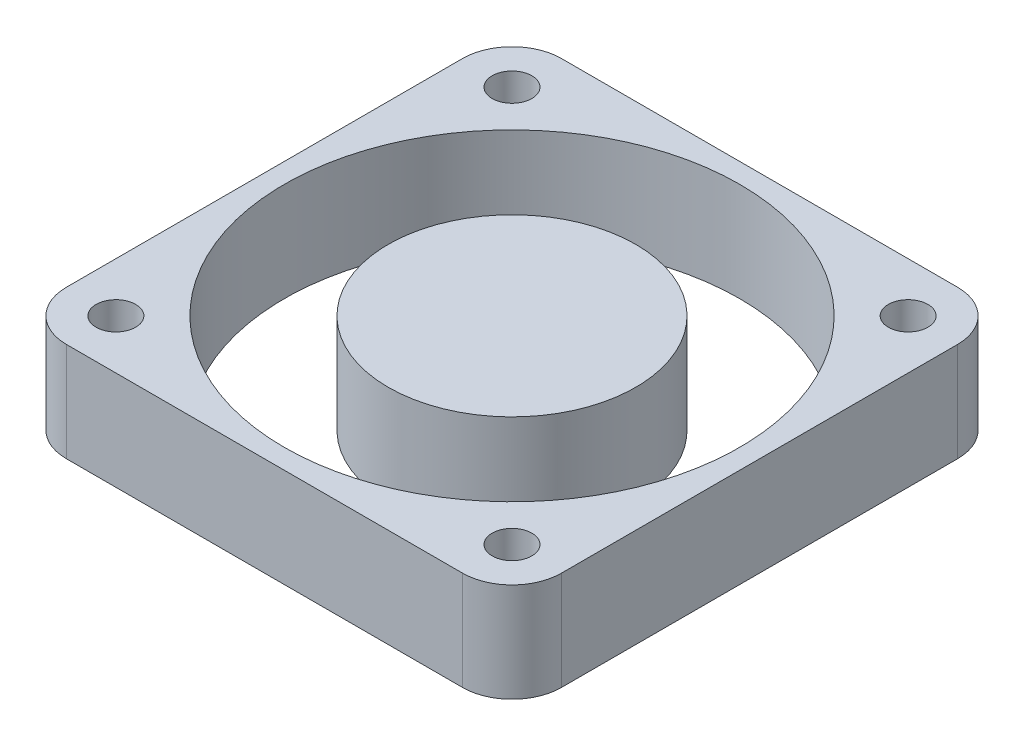
SolidWorks part; units mm, degrees
ref_plane "前视基准面" through (0, 0, 0) normal (0, 0, 1) x (1, 0, 0)
ref_plane "上视基准面" through (0, 0, 0) normal (0, 1, 0) x (1, 0, 0)
ref_plane "右视基准面" through (0, 0, 0) normal (1, 0, 0) x (0, 0, -1)
sketch "草图1" plane through (0, 0, 0) normal (0, 1, 0) x (1, 0, 0)
  line L0 (0, 74.7112) -> (0, -68.6123) construction
  line L1 (-20, 25) -> (20, 25)
  line L2 (-25, 20) -> (-25, -20)
  line L3 (-20, -25) -> (20, -25)
  line L4 (25, 20) -> (25, -20)
  line L5 (-53.6701, 0) -> (64.953, 0) construction
  arc A0 (25, 20) -> (20, 25) centre (20, 20) ccw
  arc A1 (-25, 20) -> (-20, 25) centre (-20, 20) cw
  arc A2 (-20, -25) -> (-25, -20) centre (-20, -20) cw
  arc A3 (25, -20) -> (20, -25) centre (20, -20) cw
  point P11 (25, 25)
  point P14 (-25, 25)
  point P17 (-25, -25)
  dimension "D3" = 5
  dimension "D4" = 5
  dimension "D1" = 50
  dimension "D2" = 50
extrude "拉伸1" add sketch "草图1" along normal blind 10
sketch "草图2" plane through (0, 10, 0) normal (0, 1, 0) x (-1, 0, 0)
  line L10 (-60.6024, 0) -> (52.7191, 0) construction
  line L11 (0, -57.861) -> (0, 57.0129) construction
  line L12 (-20, -23) -> (20, -23)
  line L13 (-23, 20) -> (-23, -20)
  line L14 (20, 23) -> (-20, 23)
  line L15 (23, -20) -> (23, 20)
  line L16 (-20, -23) -> (20, -23)
  line L17 (-23, 20) -> (-23, -20)
  line L18 (20, 23) -> (-20, 23)
  line L19 (23, -20) -> (23, 20)
  circle A8 centre (0, 0) radius 12.5
  arc A12 (-23, -20) -> (-20, -23) centre (-20, -20) ccw
  arc A13 (20, -23) -> (23, -20) centre (20, -20) ccw
  arc A14 (-20, 23) -> (-23, 20) centre (-20, 20) ccw
  arc A15 (23, 20) -> (20, 23) centre (20, 20) ccw
  arc A16 (-23, -20) -> (-20, -23) centre (-20, -20) ccw
  arc A17 (20, -23) -> (23, -20) centre (20, -20) ccw
  arc A18 (-20, 23) -> (-23, 20) centre (-20, 20) ccw
  arc A19 (23, 20) -> (20, 23) centre (20, 20) ccw
  dimension "D2" = 25
  dimension "D1" = 2
extrude "切除-拉伸1" cut sketch "草图2" against normal blind 17
sketch "草图3" plane through (0, 10, 0) normal (0, 1, 0) x (-1, 0, 0)
  line L0 (25, -20) -> (25, 20) construction
  line L1 (20, 25) -> (-20, 25) construction
  line L2 (-25, 20) -> (-25, -20) construction
  line L3 (-20, -25) -> (20, -25) construction
  line L4 (25, -20) -> (25, 20)
  line L5 (20, 25) -> (-20, 25)
  line L6 (-25, 20) -> (-25, -20)
  line L7 (-20, -25) -> (20, -25)
  circle A0 centre (0, 0) radius 23
  arc A1 (20, -25) -> (25, -20) centre (20, -20) ccw construction
  arc A2 (25, 20) -> (20, 25) centre (20, 20) ccw construction
  arc A3 (-20, 25) -> (-25, 20) centre (-20, 20) ccw construction
  arc A4 (-25, -20) -> (-20, -25) centre (-20, -20) ccw construction
  arc A5 (20, -25) -> (25, -20) centre (20, -20) ccw
  arc A6 (25, 20) -> (20, 25) centre (20, 20) ccw
  arc A7 (-20, 25) -> (-25, 20) centre (-20, 20) ccw
  arc A8 (-25, -20) -> (-20, -25) centre (-20, -20) ccw
  dimension "D1" = 46
extrude "拉伸3" add sketch "草图3" against normal up to surface (10 mm away) up to face at (0, 0, 0)
sketch "草图4" plane through (0, 10, 0) normal (0, 1, 0) x (-1, 0, 0)
  line L0 (-49.3843, 0) -> (58.2292, 0) construction
  line L1 (0, -54.1753) -> (0, 51.7798) construction
  circle A0 centre (-20, -20) radius 2
  circle A1 centre (-20, 20) radius 2
  circle A2 centre (20, 20) radius 2
  circle A3 centre (20, -20) radius 2
  dimension "D1" = 4
  dimension "D2" = 40
  dimension "D3" = 40
extrude "切除-拉伸2" cut sketch "草图4" against normal up to surface (10 mm away) up to face at (0, 0, 23)
